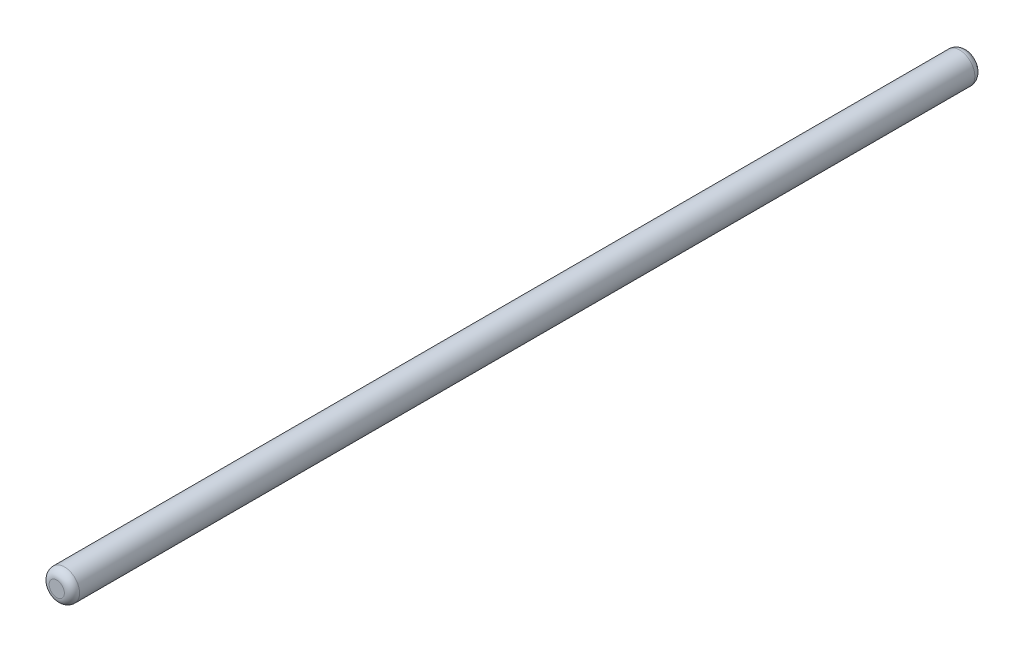
SolidWorks part; units mm, degrees
ref_plane "Front Plane" through (0, 0, 0) normal (0, 0, 1) x (1, 0, 0)
ref_plane "Top Plane" through (0, 0, 0) normal (0, 1, 0) x (1, 0, 0)
ref_plane "Right Plane" through (0, 0, 0) normal (1, 0, 0) x (0, 0, -1)
sketch "Sketch1" plane through (0, 0, 0) normal (0, 0, 1) x (1, 0, 0)
  circle A0 centre (0, 0) radius 4
  dimension "D1" = 8
extrude "Boss-Extrude1" add sketch "Sketch1" along normal blind 239
fillet "Fillet1" radius 2 2 edges at (4, 0, 239) (4, 0, 0)
